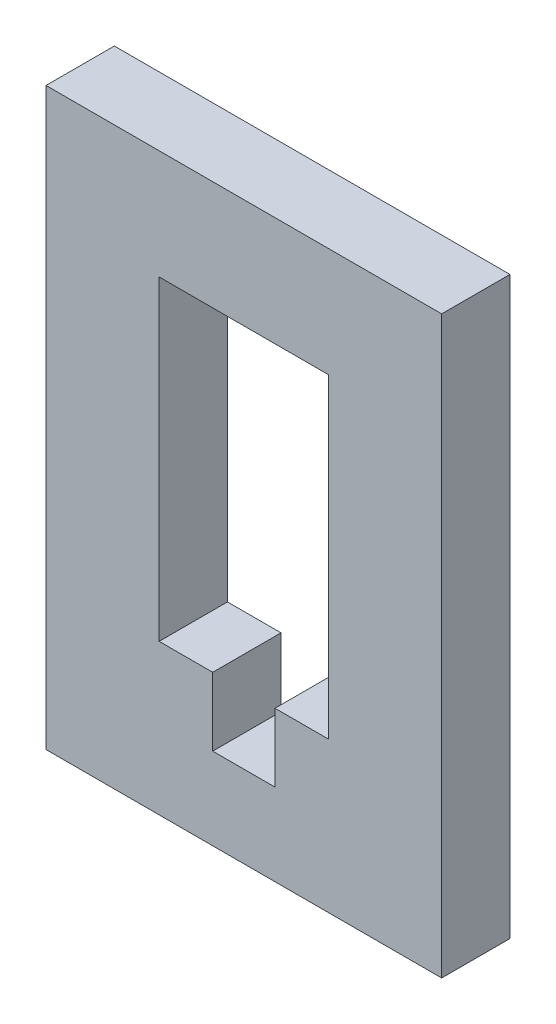
SolidWorks part; units mm, degrees
ref_plane "Front Plane" through (0, 0, 0) normal (0, 0, 1) x (1, 0, 0)
ref_plane "Top Plane" through (0, 0, 0) normal (0, 1, 0) x (1, 0, 0)
ref_plane "Right Plane" through (0, 0, 0) normal (1, 0, 0) x (0, 0, -1)
sketch "Sketch1" plane through (0, 0, 0) normal (0, 0, 1) x (1, 0, 0)
  line L1 (-18.5582, 31.0897) -> (10.4018, 31.0897)
  line L2 (-18.5582, 31.0897) -> (-18.5582, 20.0897)
  line L3 (-18.5582, 20.0897) -> (10.4018, 20.0897)
  line L4 (10.4018, 31.0897) -> (10.4018, 20.0897)
  dimension "D1" = 28.96
  dimension "D2" = 11
extrude "Boss-Extrude1" add sketch "Sketch1" along normal blind 5
sketch "Sketch2" plane through (0, 31.0897, 0) normal (0, 1, 0) x (1, 0, 0)
  line L0 (-18.5582, 0) -> (-10.2782, 0)
  line L1 (10.4018, 0) -> (-18.5582, 0) construction
  line L2 (-10.2782, 0) -> (-10.2782, -5)
  line L3 (10.4018, -5) -> (-18.5582, -5) construction
  line L4 (-10.2782, -5) -> (-18.5582, -5)
  line L5 (-18.5582, -5) -> (-18.5582, 0)
  line L6 (10.4018, 0) -> (2.1218, 0)
  line L7 (2.1218, 0) -> (2.1218, -5)
  line L8 (2.1218, -5) -> (10.4018, -5)
  line L9 (10.4018, -5) -> (10.4018, 0)
  dimension "D1" = 12.4
extrude "Boss-Extrude2" add sketch "Sketch2" along normal blind 23.1
sketch "Sketch3" plane through (0, 54.1897, 0) normal (0, 1, 0) x (1, 0, 0)
  line L1 (-18.5582, 0) -> (10.4018, 0)
  line L2 (-18.5582, 0) -> (-18.5582, -5)
  line L3 (-18.5582, -5) -> (10.4018, -5)
  line L4 (10.4018, 0) -> (10.4018, -5)
extrude "Boss-Extrude3" add sketch "Sketch3" along normal blind 8
sketch "Sketch4" plane through (0, 31.0897, 0) normal (0, 1, 0) x (1, 0, 0)
  line L0 (10.4018, 0) -> (-18.5582, 0) construction
  line L1 (-6.3582, 0) -> (-1.7982, 0)
  line L2 (-6.3582, 0) -> (-6.3582, -5)
  line L3 (-6.3582, -5) -> (-1.7982, -5)
  line L4 (-1.7982, 0) -> (-1.7982, -5)
  line L5 (-18.5582, -5) -> (10.4018, -5) construction
  line L6 (-18.5582, 0) -> (-18.5582, -5) construction
  line L7 (10.4018, -5) -> (10.4018, 0) construction
  dimension "D1" = 12.2
  dimension "D2" = 12.2
extrude "Cut-Extrude1" cut sketch "Sketch4" against normal blind 5
